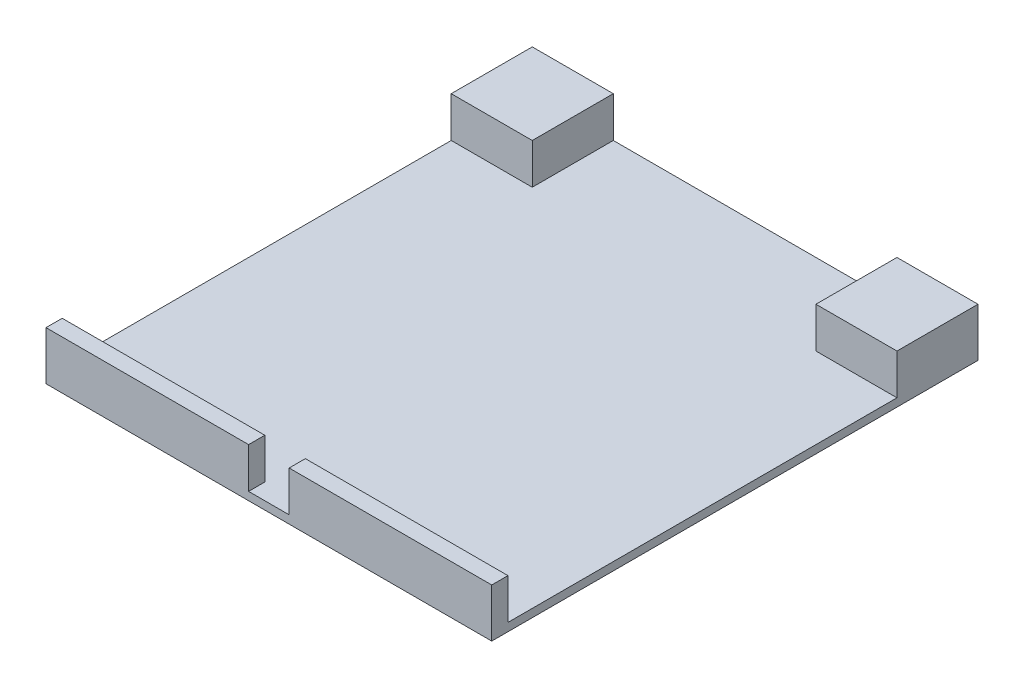
SolidWorks part; units mm, degrees
ref_plane "Front Plane" through (0, 0, 0) normal (0, 0, 1) x (1, 0, 0)
ref_plane "Top Plane" through (0, 0, 0) normal (0, 1, 0) x (1, 0, 0)
ref_plane "Right Plane" through (0, 0, 0) normal (1, 0, 0) x (0, 0, -1)
sketch "Sketch1" plane through (0, 0, 0) normal (0, 1, 0) x (1, 0, 0)
  line L1 (-34.925, 38.1) -> (34.925, 38.1)
  line L2 (-34.925, 38.1) -> (-34.925, -38.1)
  line L3 (-34.925, -38.1) -> (34.925, -38.1)
  line L4 (34.925, 38.1) -> (34.925, -38.1)
  line L5 (-34.925, 38.1) -> (34.925, -38.1) construction
  line L6 (-34.925, -38.1) -> (34.925, 38.1) construction
  point P0 (0, 0)
  dimension "D1" = 69.85
  dimension "D2" = 76.2
extrude "Boss-Extrude1" add sketch "Sketch1" along normal blind 1.27
sketch "Sketch2" plane through (0, 1.27, 0) normal (0, 1, 0) x (1, 0, 0)
  line L0 (34.925, 38.1) -> (-34.925, 38.1) construction
  line L1 (-34.925, 38.1) -> (-22.225, 38.1)
  line L2 (-34.925, 38.1) -> (-34.925, 25.4)
  line L3 (-34.925, 25.4) -> (-22.225, 25.4)
  line L4 (-22.225, 38.1) -> (-22.225, 25.4)
  line L5 (-34.925, 38.1) -> (-22.225, 25.4) construction
  line L6 (-34.925, 25.4) -> (-22.225, 38.1) construction
  line L7 (-34.925, 38.1) -> (-34.925, -38.1) construction
  line L8 (22.225, 38.1) -> (34.925, 38.1)
  line L9 (22.225, 38.1) -> (22.225, 25.4)
  line L10 (22.225, 25.4) -> (34.925, 25.4)
  line L11 (34.925, 38.1) -> (34.925, 25.4)
  line L12 (34.925, -38.1) -> (34.925, 38.1) construction
  line L13 (-34.925, -38.1) -> (34.925, -38.1) construction
  line L14 (3.175, -35.56) -> (34.925, -35.56)
  line L15 (3.175, -35.56) -> (3.175, -38.1)
  line L16 (3.175, -38.1) -> (34.925, -38.1)
  line L17 (34.925, -35.56) -> (34.925, -38.1)
  line L18 (3.175, -35.56) -> (34.925, -38.1) construction
  line L19 (3.175, -38.1) -> (34.925, -35.56) construction
  line L20 (-34.925, -35.56) -> (-3.175, -35.56)
  line L21 (-34.925, -35.56) -> (-34.925, -38.1)
  line L22 (-34.925, -38.1) -> (-3.175, -38.1)
  line L23 (-3.175, -35.56) -> (-3.175, -38.1)
  point P0 (-28.575, 31.75)
  point P20 (19.05, -36.83)
  dimension "D1" = 12.7
  dimension "D2" = 12.7
  dimension "D3" = 31.75
  dimension "D4" = 2.54
extrude "Boss-Extrude2" add sketch "Sketch2" along normal blind 6.35
